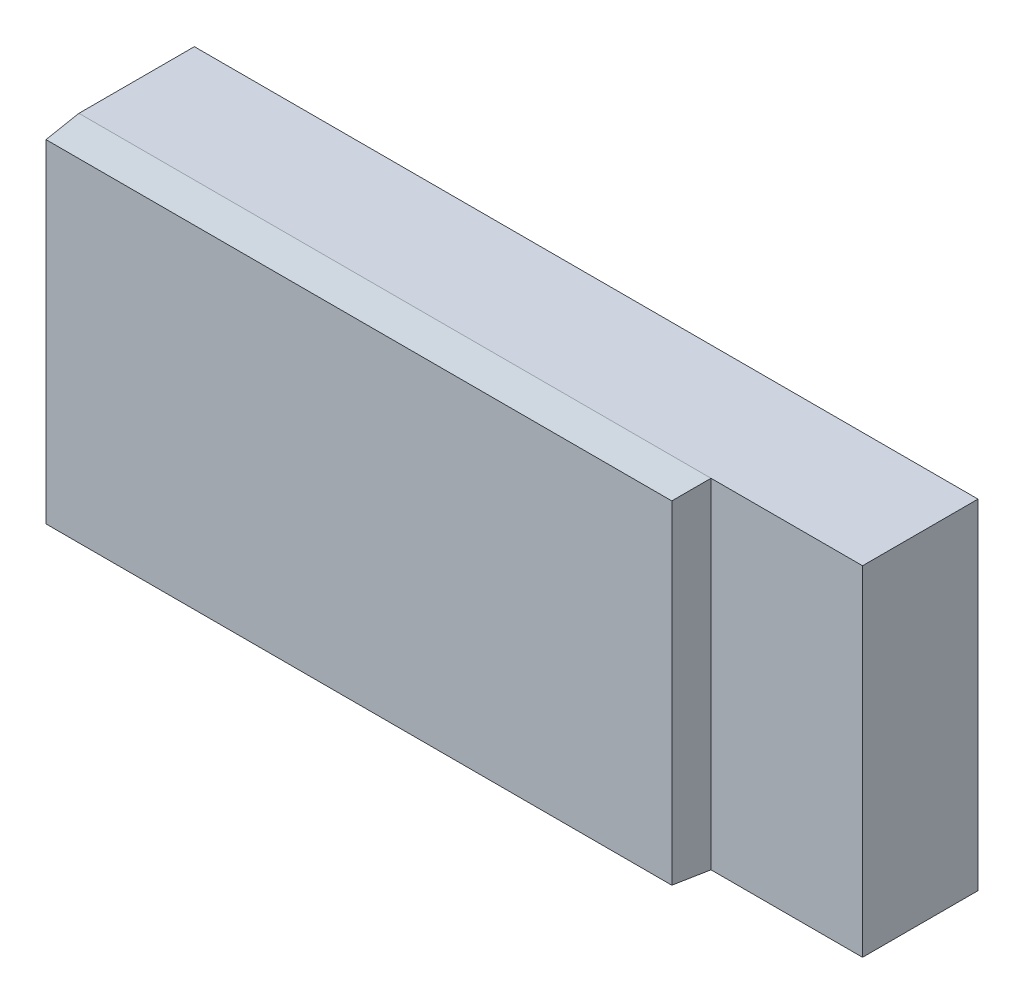
SolidWorks part; units mm, degrees
ref_plane "Front Plane" through (0, 0, 0) normal (0, 0, 1) x (1, 0, 0)
ref_plane "Top Plane" through (0, 0, 0) normal (0, 1, 0) x (1, 0, 0)
ref_plane "Right Plane" through (0, 0, 0) normal (1, 0, 0) x (0, 0, -1)
sketch "Sketch1" plane through (0, 0, 0) normal (0, 0, 1) x (1, 0, 0)
  line L1 (-13.575, -5.875) -> (13.575, -5.875)
  line L2 (-13.575, -5.875) -> (-13.575, 5.875)
  line L3 (-13.575, 5.875) -> (13.575, 5.875)
  line L4 (13.575, -5.875) -> (13.575, 5.875)
  line L5 (-13.575, -5.875) -> (13.575, 5.875) construction
  line L6 (-13.575, 5.875) -> (13.575, -5.875) construction
  point P0 (0, 0)
  dimension "D1" = 27.15
  dimension "D2" = 11.75
extrude "Boss-Extrude1" add sketch "Sketch1" along normal blind 4
sketch "Sketch2" plane through (0, 0, 4) normal (0, 0, 1) x (1, 0, 0)
  line L0 (-13.575, -5.875) -> (13.575, -5.875) construction
  line L1 (-13.575, 5.875) -> (8.325, 5.875)
  line L2 (-13.575, 5.875) -> (-13.575, -5.875)
  line L3 (-13.575, -5.875) -> (8.325, -5.875)
  line L4 (8.325, 5.875) -> (8.325, -5.875)
  line L5 (13.575, -5.875) -> (13.575, 5.875) construction
  dimension "D1" = 5.25
extrude "Boss-Extrude2" add sketch "Sketch2" along normal blind 1.25 draft 5
